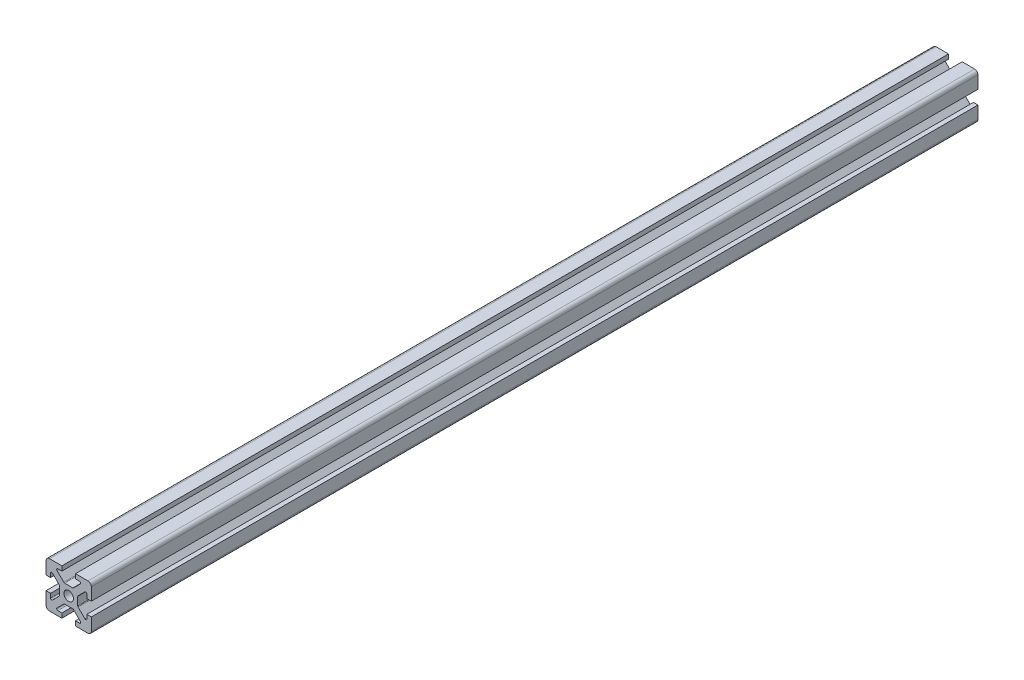
SolidWorks part; units mm, degrees
ref_plane "前基準面" through (0, 0, 0) normal (0, 0, 1) x (1, 0, 0)
ref_plane "上基準面" through (0, 0, 0) normal (0, 1, 0) x (1, 0, 0)
ref_plane "右基準面" through (0, 0, 0) normal (1, 0, 0) x (0, 0, -1)
sketch "草圖1" plane through (0, 0, 0) normal (0, 0, 1) x (1, 0, 0)
  line L0 (0, -20.6493) -> (0, 20.6493) construction
  line L1 (-10, 10) -> (10, 10)
  line L2 (-10, 10) -> (-10, -10)
  line L3 (-10, -10) -> (10, -10)
  line L4 (10, 10) -> (10, -10)
  line L5 (24.1073, 0) -> (-24.1073, 0) construction
  dimension "D1" = 20
  dimension "D2" = 20
  dimension "D3" = 10
  dimension "D4" = 10
extrude "填料-伸長1" add sketch "草圖1" along normal blind 391
fillet "圓角1" radius 1.5 4 edges at (10, -10, 195.5) (10, 10, 195.5) (-10, -10, 195.5) (-10, 10, 195.5)
sketch "草圖2" plane through (0, 0, 391) normal (0, 0, 1) x (1, 0, 0)
  line L0 (10, 3) -> (8, 3)
  line L1 (10, -8.5) -> (10, 8.5) construction
  line L2 (8, 3) -> (8, 4.7929)
  line L3 (7.1464, 5.1464) -> (4.1464, 2.1464)
  line L4 (4, 1.7929) -> (4, -1.7929)
  line L5 (4.1464, -2.1464) -> (7.1464, -5.1464)
  line L6 (8, -4.7929) -> (8, -3)
  line L7 (8, -3) -> (10, -3)
  line L8 (10, -3) -> (10, 3)
  line L9 (-8.5, -10) -> (8.5, -10) construction
  line L10 (-3, -10) -> (3, -10)
  line L11 (3, -10) -> (3, -8)
  line L12 (3, -8) -> (4.7929, -8)
  line L13 (5.1464, -7.1464) -> (2.1464, -4.1464)
  line L14 (1.7929, -4) -> (-1.7929, -4)
  line L15 (-2.1464, -4.1464) -> (-5.1464, -7.1464)
  line L16 (-4.7929, -8) -> (-3, -8)
  line L17 (-3, -8) -> (-3, -10)
  line L18 (-10, 3) -> (-10, -3)
  line L19 (-10, -3) -> (-8, -3)
  line L20 (-8, -3) -> (-8, -4.7929)
  line L21 (-7.1464, -5.1464) -> (-4.1464, -2.1464)
  line L22 (-4, -1.7929) -> (-4, 1.7929)
  line L23 (-4.1464, 2.1464) -> (-7.1464, 5.1464)
  line L24 (-8, 4.7929) -> (-8, 3)
  line L25 (-8, 3) -> (-10, 3)
  line L26 (3, 10) -> (-3, 10)
  line L27 (-3, 10) -> (-3, 8)
  line L28 (-3, 8) -> (-4.7929, 8)
  line L29 (-5.1464, 7.1464) -> (-2.1464, 4.1464)
  line L30 (-1.7929, 4) -> (1.7929, 4)
  line L31 (2.1464, 4.1464) -> (5.1464, 7.1464)
  line L32 (4.7929, 8) -> (3, 8)
  line L33 (3, 8) -> (3, 10)
  circle A0 centre (0, 0) radius 2.1
  arc A1 (7.1464, -5.1464) -> (8, -4.7929) centre (7.5, -4.7929) ccw
  arc A2 (4, -1.7929) -> (4.1464, -2.1464) centre (4.5, -1.7929) ccw
  arc A3 (4.1464, 2.1464) -> (4, 1.7929) centre (4.5, 1.7929) ccw
  arc A4 (8, 4.7929) -> (7.1464, 5.1464) centre (7.5, 4.7929) ccw
  arc A5 (4.7929, -8) -> (5.1464, -7.1464) centre (4.7929, -7.5) ccw
  arc A6 (2.1464, -4.1464) -> (1.7929, -4) centre (1.7929, -4.5) ccw
  arc A7 (-1.7929, -4) -> (-2.1464, -4.1464) centre (-1.7929, -4.5) ccw
  arc A8 (-5.1464, -7.1464) -> (-4.7929, -8) centre (-4.7929, -7.5) ccw
  arc A9 (-8, -4.7929) -> (-7.1464, -5.1464) centre (-7.5, -4.7929) ccw
  arc A10 (-4.1464, -2.1464) -> (-4, -1.7929) centre (-4.5, -1.7929) ccw
  arc A11 (-4, 1.7929) -> (-4.1464, 2.1464) centre (-4.5, 1.7929) ccw
  arc A12 (-7.1464, 5.1464) -> (-8, 4.7929) centre (-7.5, 4.7929) ccw
  arc A13 (-4.7929, 8) -> (-5.1464, 7.1464) centre (-4.7929, 7.5) ccw
  arc A14 (-2.1464, 4.1464) -> (-1.7929, 4) centre (-1.7929, 4.5) ccw
  arc A15 (1.7929, 4) -> (2.1464, 4.1464) centre (1.7929, 4.5) ccw
  arc A16 (5.1464, 7.1464) -> (4.7929, 8) centre (4.7929, 7.5) ccw
  point P17 (8, -6)
  point P24 (8, 6)
  point P76 (0, 0)
  dimension "D1" = 4.2
  dimension "D10" = 0.5
  dimension "D2" = 6
  dimension "D3" = 3
  dimension "D4" = 3
  dimension "D5" = 7
  dimension "D6" = 4
  dimension "D7" = 2
  dimension "D8" = 45
  dimension "D9" = 2
  dimension "D11" = 4
extrude "除料-伸長1" cut sketch "草圖2" against normal through all
